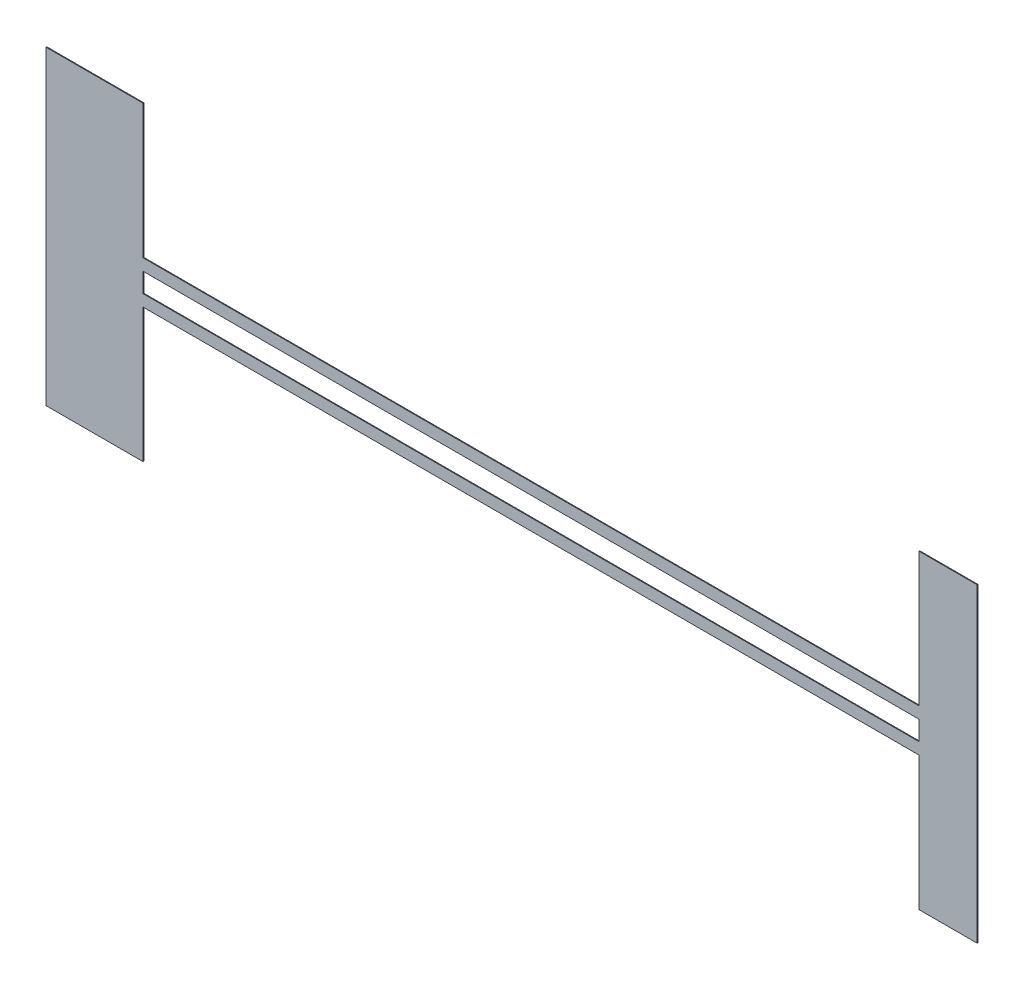
SolidWorks part; units mm, degrees
ref_plane "Front Plane" through (0, 0, 0) normal (0, 0, 1) x (1, 0, 0)
ref_plane "Top Plane" through (0, 0, 0) normal (0, 1, 0) x (1, 0, 0)
ref_plane "Right Plane" through (0, 0, 0) normal (1, 0, 0) x (0, 0, -1)
sketch "Sketch2" plane through (0, 0, 0) normal (0, 0, 1) x (1, 0, 0)
  line L0 (-1987.3494, 0) -> (1987.3494, 0) construction
  line L1 (0, 1542.0431) -> (0, -1542.0431) construction
  line L2 (250, 2000) -> (250, 275)
  line L3 (-1000, 2000) -> (250, 2000)
  line L4 (-1000, 2000) -> (-1000, -2000)
  line L5 (-1000, -2000) -> (250, -2000)
  line L6 (11000, 2000) -> (11000, -2000)
  line L7 (250, 125) -> (10250, 125)
  line L8 (250, 125) -> (250, -125)
  line L9 (250, -125) -> (10250, -125)
  line L10 (10250, 125) -> (10250, -125)
  line L11 (250, -2000) -> (250, -275)
  line L12 (250, 275) -> (10250, 275)
  line L13 (10250, 275) -> (10250, 2000)
  line L14 (10250, 2000) -> (11000, 2000)
  line L15 (250, -275) -> (10250, -275)
  line L16 (10250, -275) -> (10250, -2000)
  line L17 (10250, -2000) -> (11000, -2000)
  dimension "D1" = 12000
  dimension "D2" = 4000
  dimension "D3" = 2000
  dimension "D4" = 1000
  dimension "D5" = 250
  dimension "D6" = 125
  dimension "D7" = 250
  dimension "D8" = 10000
  dimension "D9" = 150
  dimension "D10" = 150
extrude "Boss-Extrude1" add sketch "Sketch2" against normal blind 10
